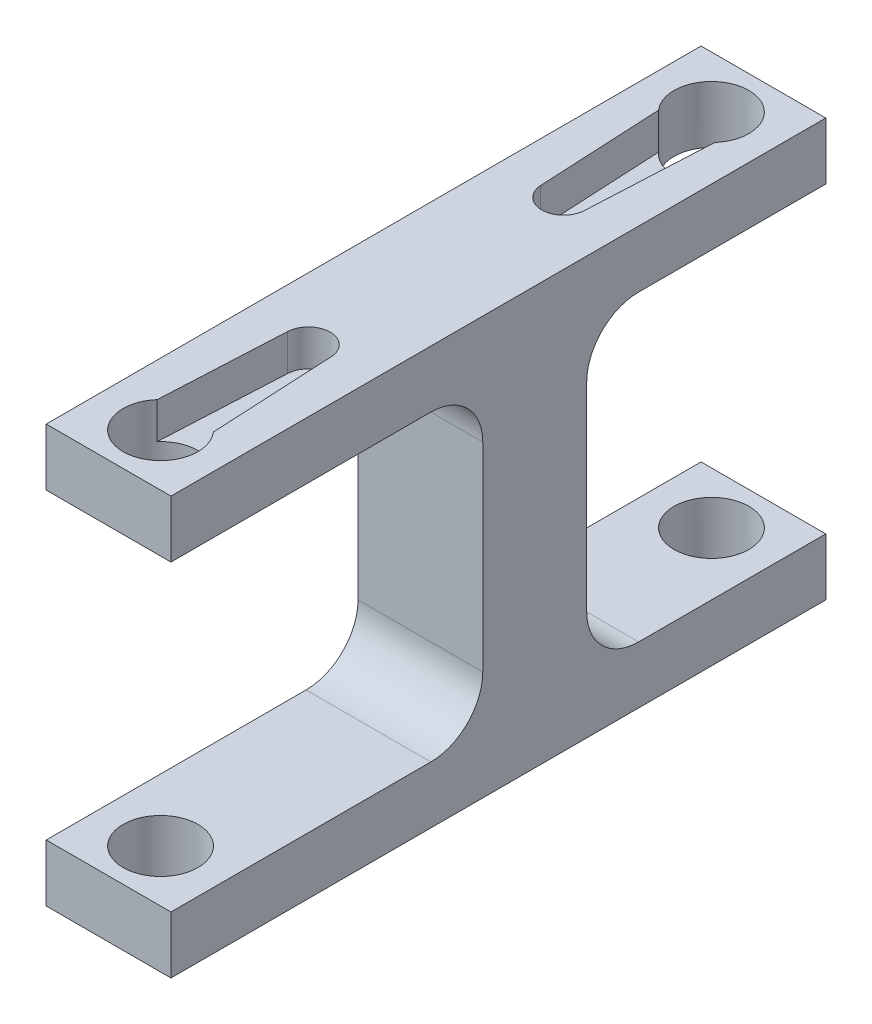
SolidWorks part; units mm, degrees
ref_plane "Front Plane" through (0, 0, 0) normal (0, 0, 1) x (1, 0, 0)
ref_plane "Top Plane" through (0, 0, 0) normal (0, 1, 0) x (1, 0, 0)
ref_plane "Right Plane" through (0, 0, 0) normal (1, 0, 0) x (0, 0, -1)
sketch "Sketch2" plane through (0, 0, 0) normal (0, 0, 1) x (1, 0, 0)
  line L1 (-8.6116, 0.9665) -> (3.3884, 0.9665)
  line L2 (-8.6116, 0.9665) -> (-8.6116, -39.1835)
  line L3 (-8.6116, -39.1835) -> (3.3884, -39.1835)
  line L4 (3.3884, 0.9665) -> (3.3884, -39.1835)
  dimension "D1" = 12
  dimension "D2" = 40.15
extrude "Boss-Extrude2" add sketch "Sketch2" along normal blind 2.5
sketch "Sketch11" plane through (0, 0, 2.5) normal (0, 0, 1) x (1, 0, 0)
  line L0 (3.3884, 0.9665) -> (3.3884, -39.1835) construction
  line L1 (-8.6116, 0.9665) -> (3.3884, 0.9665)
  line L2 (-8.6116, 0.9665) -> (-8.6116, -4.5335)
  line L3 (-8.6116, -4.5335) -> (3.3884, -4.5335)
  line L4 (3.3884, 0.9665) -> (3.3884, -4.5335)
  line L6 (-8.6116, -39.1835) -> (3.3884, -39.1835)
  line L7 (-8.6116, -39.1835) -> (-8.6116, -33.6835)
  line L8 (-8.6116, -33.6835) -> (3.3884, -33.6835)
  line L9 (3.3884, -39.1835) -> (3.3884, -33.6835)
  dimension "D1" = 5.5
  dimension "D2" = 5.5
extrude "Boss-Extrude8" add sketch "Sketch11" along normal blind 30
sketch "Sketch12" plane through (0, 0.9665, 0) normal (0, 1, 0) x (1, 0, 0)
  line L2 (-0.5143, -13.1688) -> (0.0884, -25.1188)
  line L6 (-5.3116, -25.1188) -> (-4.7089, -13.1688)
  line L7 (3.3884, -32.5) -> (-8.6116, -32.5) construction
  line L8 (-2.6116, -27.5) -> (-2.6116, -32.5) construction
  arc A4 (-5.3116, -25.1188) -> (0.0884, -25.1188) centre (-2.6116, -27.5) ccw
  arc A5 (-0.5143, -13.1688) -> (-4.7089, -13.1688) centre (-2.6116, -13.2745) ccw
  dimension "D1" = 3.6
  dimension "D5" = 2.1
  dimension "D2" = 5
  dimension "D3" = 11.95
  dimension "D4" = 11.95
  dimension "D6" = 5.4
extrude "Cut-Extrude1" cut sketch "Sketch12" against normal blind 3.5
sketch "Sketch14" plane through (0, 0, 0) normal (0, 0, -1) x (-1, 0, 0)
  line L9 (-3.3884, 0.9665) -> (8.6116, 0.9665)
  line L10 (-3.3884, 0.9665) -> (-3.3884, -39.1835)
  line L11 (-3.3884, -39.1835) -> (8.6116, -39.1835)
  line L12 (8.6116, 0.9665) -> (8.6116, -39.1835)
extrude "Boss-Extrude9" add sketch "Sketch14" along normal blind 7.5
sketch "Sketch16" plane through (0, 0, -7.5) normal (0, 0, -1) x (-1, 0, 0)
  line L0 (8.6116, -36.1835) -> (8.6116, 0.9665) construction
  line L1 (-3.3884, 0.9665) -> (8.6116, 0.9665)
  line L2 (-3.3884, 0.9665) -> (-3.3884, -4.5335)
  line L3 (-3.3884, -4.5335) -> (8.6116, -4.5335)
  line L4 (8.6116, 0.9665) -> (8.6116, -4.5335)
  line L12 (8.6116, -39.1835) -> (8.6116, 0.9665) construction
  line L13 (-3.3884, -39.1835) -> (8.6116, -39.1835)
  line L14 (-3.3884, -39.1835) -> (-3.3884, -33.6835)
  line L15 (-3.3884, -33.6835) -> (8.6116, -33.6835)
  line L16 (8.6116, -39.1835) -> (8.6116, -33.6835)
  dimension "D1" = 5.5
  dimension "D2" = 5.5
extrude "Boss-Extrude11" add sketch "Sketch16" along normal blind 23
sketch "Sketch20" plane through (0, 0.9665, 0) normal (0, 1, 0) x (1, 0, 0)
  line L4 (-4.7089, 11.1688) -> (-5.3116, 23.1188)
  line L8 (0.0884, 23.1188) -> (-0.5143, 11.1688)
  line L9 (-8.6116, 30.5) -> (3.3884, 30.5) construction
  line L10 (-2.6116, 25.5) -> (-2.6116, 30.5) construction
  arc A6 (0.0884, 23.1188) -> (-5.3116, 23.1188) centre (-2.6116, 25.5) ccw
  arc A7 (-4.7089, 11.1688) -> (-0.5143, 11.1688) centre (-2.6116, 11.2745) ccw
  dimension "D1" = 3.6
  dimension "D5" = 2.1
  dimension "D2" = 5
  dimension "D3" = 11.95
  dimension "D4" = 11.95
  dimension "D6" = 5.4
extrude "Cut-Extrude4" cut sketch "Sketch20" against normal blind 3.5
sketch "Sketch22" plane through (0, 0.9665, 0) normal (0, 1, 0) x (1, 0, 0)
  circle A0 centre (-2.6116, -27.5) radius 3.6
  dimension "D1" = 7.2
extrude "Cut-Extrude6" cut sketch "Sketch22" against normal through all
sketch "Sketch23" plane through (0, 0.9665, 0) normal (0, 1, 0) x (1, 0, 0)
  circle A0 centre (-2.6116, 25.5) radius 3.6
  dimension "D1" = 7.2
extrude "Cut-Extrude7" cut sketch "Sketch23" against normal through all
fillet "Fillet1" radius 5 1 edges at (-2.6116, -4.5335, 2.5)
fillet "Fillet2" radius 5 1 edges at (-2.6116, -33.6835, 2.5)
fillet "Fillet3" radius 5 1 edges at (-2.6116, -4.5335, -7.5)
fillet "Fillet4" radius 5 1 edges at (-2.6116, -33.6835, -7.5)
